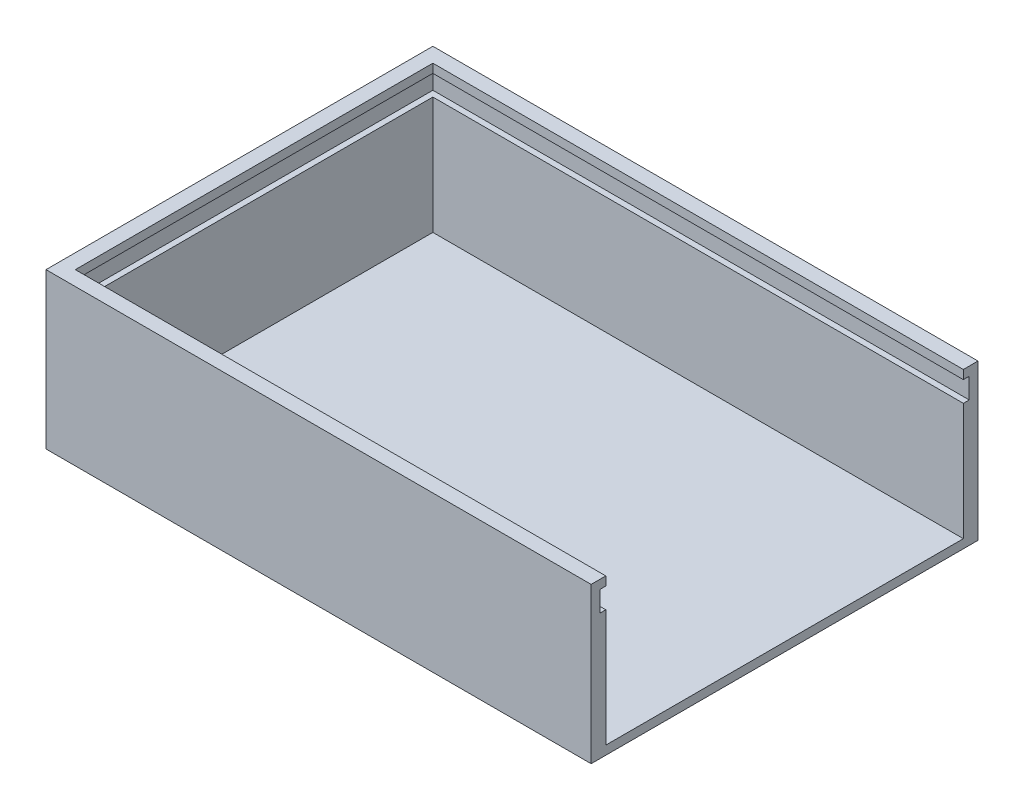
SolidWorks part; units mm, degrees
ref_plane "Front" through (0, 0, 0) normal (0, 0, 1) x (1, 0, 0)
ref_plane "Top" through (0, 0, 0) normal (0, 1, 0) x (1, 0, 0)
ref_plane "Right" through (0, 0, 0) normal (1, 0, 0) x (0, 0, -1)
sketch "Esquisse1" plane through (0, 0, 0) normal (0, 1, 0) x (1, 0, 0)
  line L1 (-93, 66) -> (93, 66)
  line L2 (-93, 66) -> (-93, -66)
  line L3 (-93, -66) -> (93, -66)
  line L4 (93, 66) -> (93, -66)
  line L5 (-93, 66) -> (93, -66) construction
  line L6 (-93, -66) -> (93, 66) construction
  point P0 (0, 0)
  dimension "D1" = 186
  dimension "D2" = 132
extrude "Boss.-Extru.1" add sketch "Esquisse1" along normal blind 3
sketch "Esquisse4" plane through (0, 3, 0) normal (0, 1, 0) x (1, 0, 0)
  line L0 (-93, 66) -> (-93, -66) construction
  line L1 (93, 66) -> (-93, 66)
  line L2 (93, 66) -> (93, 61)
  line L3 (93, 61) -> (-93, 61)
  line L4 (-93, 66) -> (-93, 61)
  line L6 (93, -66) -> (-93, -66)
  line L7 (93, -66) -> (93, -61)
  line L8 (93, -61) -> (-93, -61)
  line L9 (-93, -66) -> (-93, -61)
  line L10 (-93, -61) -> (-88, -61)
  line L11 (-93, -61) -> (-93, 61)
  line L12 (-93, 61) -> (-88, 61)
  line L13 (-88, -61) -> (-88, 61)
  line M9 (93, -66) -> (93, 66)
  line M10 (93, 66) -> (-93, 66)
  line M11 (-93, 66) -> (-93, -66)
  line M12 (-93, -66) -> (93, -66)
  dimension "D1" = 5
  dimension "D2" = 5
  dimension "D3" = 5
extrude "Boss.-Extru.4" add sketch "Esquisse4" along normal blind 50 contours L3 M9 M10 M11 | L8 L13 L3 M11 | L8 M9 M11 M12
sketch "Esquisse5" plane through (93, 0, 0) normal (1, 0, 0) x (0, 0, -1)
  line L0 (-61, 53) -> (-61, 3) construction
  line L1 (-63, 50) -> (63, 50)
  line L2 (-63, 50) -> (-63, 43)
  line L3 (-63, 43) -> (63, 43)
  line L4 (63, 50) -> (63, 43)
  line L5 (61, 53) -> (61, 3) construction
  line L6 (61, 53) -> (66, 53) construction
  dimension "D1" = 2
  dimension "D2" = 2
  dimension "D3" = 3
  dimension "D4" = 7
extrude "Enlèv. mat.-Extru.1" cut sketch "Esquisse5" against normal blind 183
